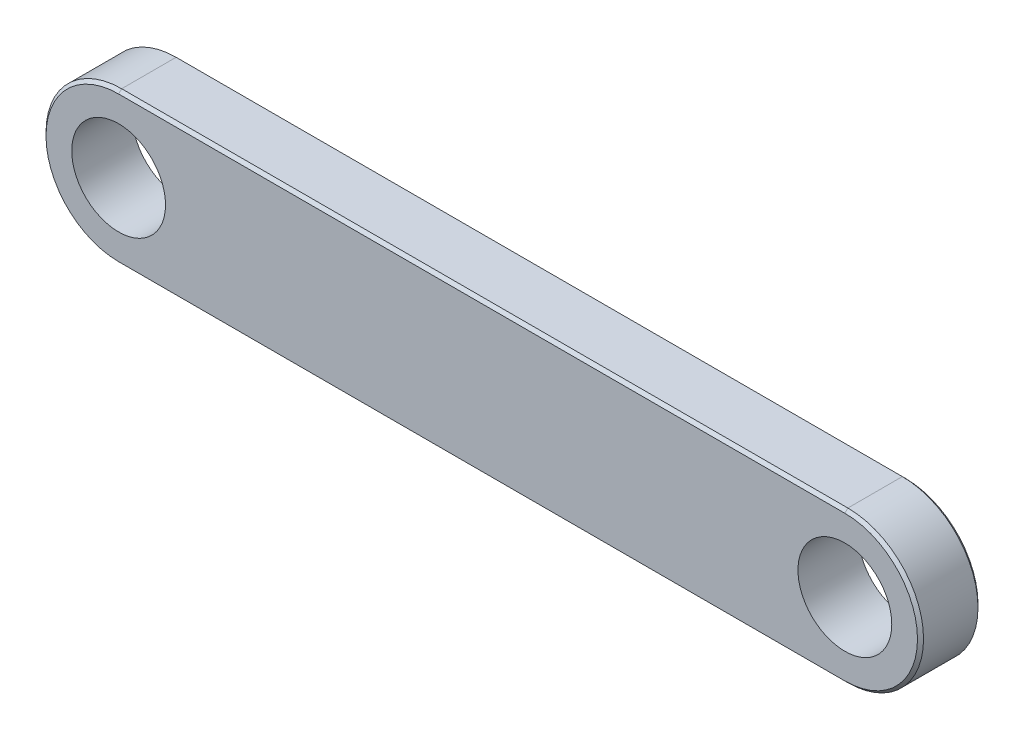
SolidWorks part; units mm, degrees
ref_plane "Front Plane" through (0, 0, 0) normal (0, 0, 1) x (1, 0, 0)
ref_plane "Top Plane" through (0, 0, 0) normal (0, 1, 0) x (1, 0, 0)
ref_plane "Right Plane" through (0, 0, 0) normal (1, 0, 0) x (0, 0, -1)
sketch "Sketch1" plane through (0, 0, 0) normal (0, 0, 1) x (1, 0, 0)
  line L0 (-12, 0) -> (12, 0) construction
  line L1 (-12, 2.5) -> (12, 2.5)
  line L2 (-12, -2.5) -> (12, -2.5)
  arc A0 (-12, 2.5) -> (-12, -2.5) centre (-12, 0) ccw
  arc A1 (12, -2.5) -> (12, 2.5) centre (12, 0) ccw
  circle A2 centre (-12, 0) radius 1.55
  circle A3 centre (12, 0) radius 1.55
  point P2 (0, 0)
  dimension "D2" = 2.5
  dimension "D3" = 3.1
  dimension "D4" = 3.1
  dimension "D1" = 24
extrude "Boss-Extrude1" add sketch "Sketch1" along normal blind 2
chamfer "Chamfer1" distance 0.1 angle 45 8 edges at (-14.5, 0, 0) (0, -2.5, 0) (14.5, 0, 0) (0, 2.5, 0) (14.5, 0, 2) (0, -2.5, 2) (-14.5, 0, 2) (0, 2.5, 2)
